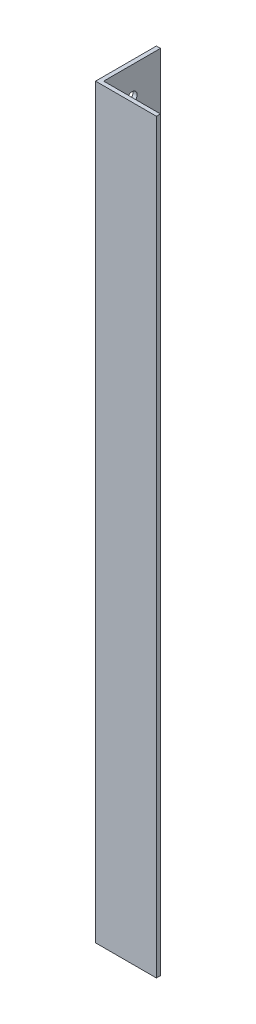
SolidWorks part; units mm, degrees
ref_plane "正面" through (0, 0, 0) normal (0, 0, 1) x (1, 0, 0)
ref_plane "平面" through (0, 0, 0) normal (0, 1, 0) x (1, 0, 0)
ref_plane "右側面" through (0, 0, 0) normal (1, 0, 0) x (0, 0, -1)
sketch "ｽｹｯﾁ1" plane through (0, 0, 0) normal (0, 1, 0) x (1, 0, 0)
  line L1 (0, 0) -> (15, 0)
  line L2 (0, 0) -> (0, -1)
  line L3 (0, -1) -> (15, -1)
  line L4 (15, 0) -> (15, -1)
  dimension "D1" = 15
  dimension "D2" = 1
sketch "ｽｹｯﾁ2" plane through (0, 0, 0) normal (0, 1, 0) x (1, 0, 0)
extrude "ﾎﾞｽ - 押し出し1" add sketch "ｽｹｯﾁ1" along normal blind 184
sketch "ｽｹｯﾁ3" plane through (0, 0, 0) normal (0, 0, -1) x (-1, 0, 0)
  line L1 (0, 184) -> (-1, 184)
  line L2 (0, 184) -> (0, 0)
  line L3 (0, 0) -> (-1, 0)
  line L4 (-1, 184) -> (-1, 0)
  dimension "D1" = 1
  dimension "D2" = 184
extrude "ﾎﾞｽ - 押し出し2" add sketch "ｽｹｯﾁ3" along normal blind 14
hole_wizard "M3x0.5 ねじ穴1" positions "ｽｹｯﾁ4" profile "ｽｹｯﾁ5" tap size "M3x0.5" standard "JIS" end condition through all
sketch "ｽｹｯﾁ4" plane through (0, 0, 0) normal (-1, 0, 0) x (0, 0, 1)
  line L0 (-14, 184) -> (1, 184) construction
  line L1 (-14, 0) -> (-14, 184) construction
  line L2 (8.25, 0) -> (-8.25, 0) construction
  point P0 (-7, 7)
  point P2 (-7, 177)
  dimension "D1" = 7
  dimension "D2" = 7
  dimension "D3" = 7
  dimension "D4" = 7
sketch "ｽｹｯﾁ5" plane through (0, 7, -7) normal (0, 1, 0) x (0, 0, 1)
  line L0 (0, 0) -> (0, 15)
  line L1 (0, 15) -> (1.25, 15)
  line L2 (1.25, 15) -> (1.25, 0)
  line L5 (1.25, 0) -> (0, 0)
  line L11 (0, -6.35) -> (0, 107.95) construction
  dimension "次ｻｰﾌｪｽまでのねじ下穴ﾄﾞﾘﾙ直径" = 2.5
  dimension "次ｻｰﾌｪｽまでのねじ下穴ﾄﾞﾘﾙの深さ" = 15
cosmetic thread "穴のねじ山1" parameters "D2"=3
cosmetic thread "穴のねじ山2" parameters "D2"=3
sketch "ｽｹｯﾁ7" plane through (0, 0, 0) normal (-1, 0, 0) x (0, 0, 1)
  line L0 (-14, 0) -> (-14, 184) construction
  line L1 (-14, 184) -> (1, 184) construction
  circle A0 centre (-7, 92) radius 2
  point P4 (-14, 92)
  dimension "D1" = 4
  dimension "D2" = 7
  dimension "D3" = 92
extrude "ｶｯﾄ - 押し出し1" cut sketch "ｽｹｯﾁ7" against normal blind 92
